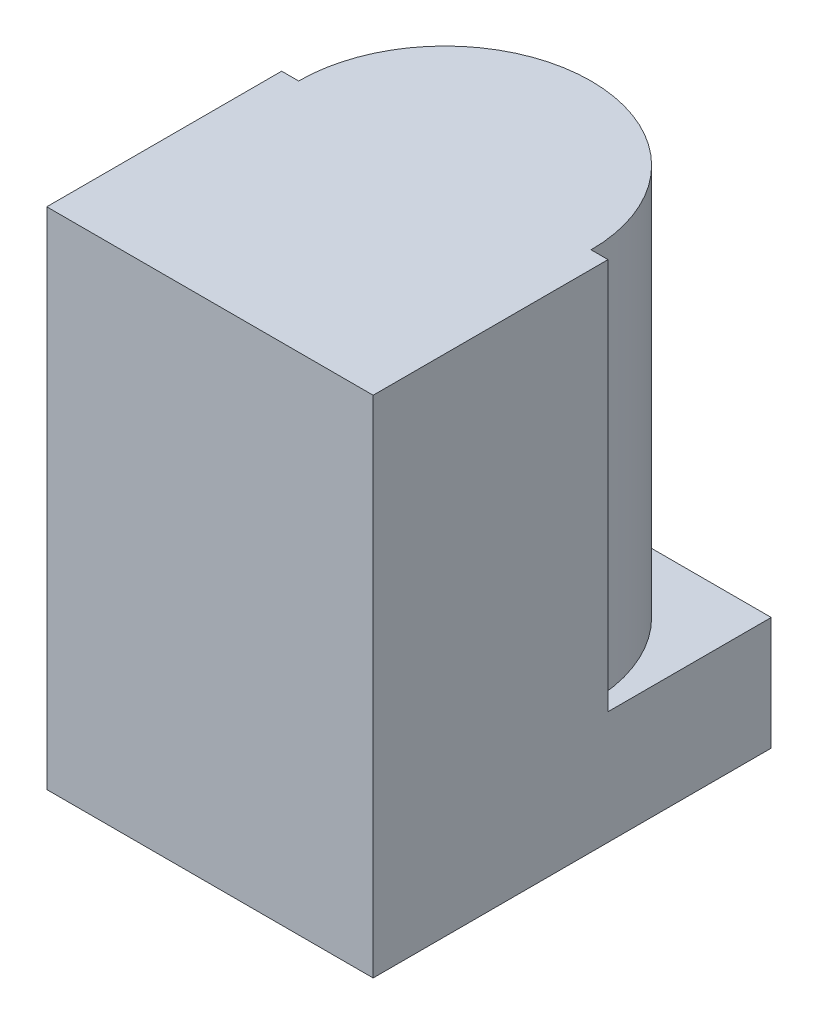
SolidWorks part; units mm, degrees
material "Nylon 6/10"
ref_plane "Front Plane" through (0, 0, 0) normal (0, 0, 1) x (1, 0, 0)
ref_plane "Top Plane" through (0, 0, 0) normal (0, 1, 0) x (1, 0, 0)
ref_plane "Right Plane" through (0, 0, 0) normal (1, 0, 0) x (0, 0, -1)
sketch "Sketch1" plane through (0, 0, 0) normal (0, 1, 0) x (1, 0, 0)
  line L1 (0, 0) -> (8.7884, 0)
  line L2 (0, 0) -> (0, 10.7188)
  line L3 (0, 10.7188) -> (8.7884, 10.7188)
  line L4 (8.7884, 0) -> (8.7884, 10.7188)
  dimension "D1" = 8.7884
  dimension "D2" = 10.7188
extrude "Boss-Extrude1" add sketch "Sketch1" along normal blind 13.589
sketch "Sketch2" plane through (0, 13.589, 0) normal (0, 1, 0) x (1, 0, 0)
  line L0 (0, 10.7188) -> (8.7884, 1.9304) construction
  line L1 (8.7884, 0) -> (8.7884, 10.7188) construction
  line L2 (8.7884, 10.7188) -> (0, 10.7188) construction
  line L3 (0.4572, 6.3246) -> (0, 6.3246)
  line L4 (0, 10.7188) -> (0, 0) construction
  line L5 (0, 6.3246) -> (0, 10.7188)
  line L6 (0, 10.7188) -> (8.7884, 10.7188)
  line L7 (8.7884, 10.7188) -> (8.7884, 6.3246)
  line L8 (8.7884, 6.3246) -> (8.3312, 6.3246)
  arc A0 (8.3312, 6.3246) -> (0.4572, 6.3246) centre (4.3942, 6.3246) ccw
  dimension "D2" = 7.874
  dimension "D1" = 45
extrude "Cut-Extrude1" cut sketch "Sketch2" against normal offset from surface (10.541 mm away) 3.048 up to face at (4.3942, 0, -5.3594)
sketch "Sketch3" plane through (0, 0, 0) normal (0, -1, 0) x (1, 0, 0)
  circle A0 centre (4.3942, -6.3246) radius 3.1115
  circle A1 centre (4.3942, -6.3246) radius 1.143
  dimension "D1" = 6.223
  dimension "D2" = 2.286
extrude "Cut-Extrude2" cut sketch "Sketch3" against normal offset from surface (11.049 mm away) 2.54 up to face at (4.3942, 13.589, -4.8726)
